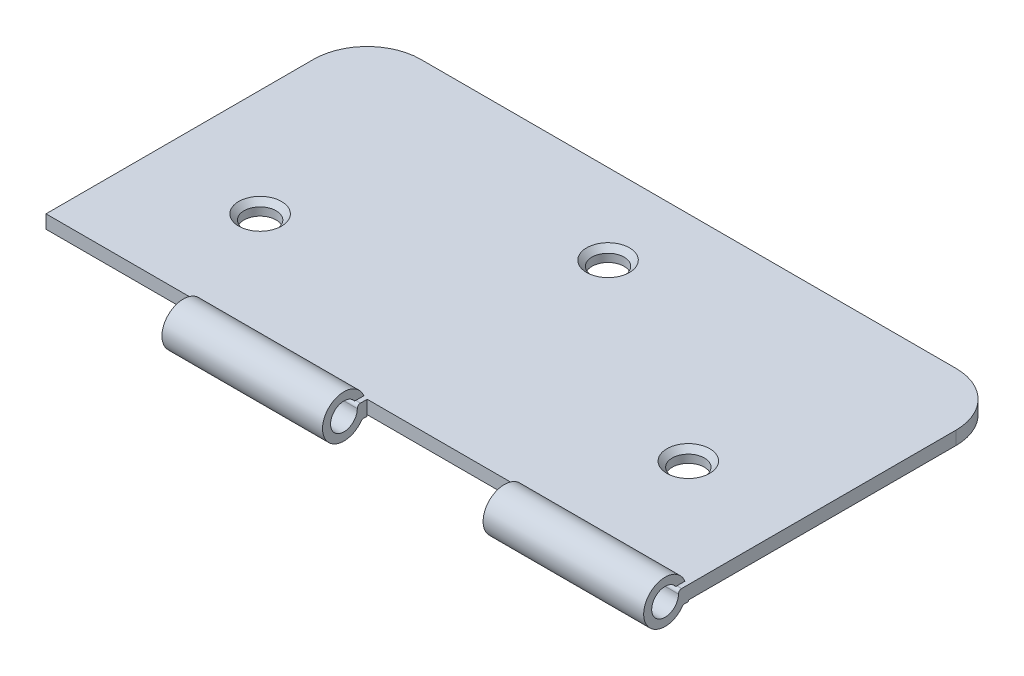
SolidWorks part; units mm, degrees
material "Brass"
ref_plane "Front Plane" through (0, 0, 0) normal (0, 0, 1) x (1, 0, 0)
ref_plane "Top Plane" through (0, 0, 0) normal (0, 1, 0) x (1, 0, 0)
ref_plane "Right Plane" through (0, 0, 0) normal (1, 0, 0) x (0, 0, -1)
sketch "Sketch1" plane through (0, 0, 0) normal (0, 1, 0) x (1, 0, 0)
  line L1 (60, 30) -> (-60, 30)
  line L2 (60, 30) -> (60, -30)
  line L3 (60, -30) -> (-60, -30)
  line L4 (-60, 30) -> (-60, -30)
  line L5 (60, 30) -> (-60, -30) construction
  line L6 (60, -30) -> (-60, 30) construction
  point P0 (0, 0)
  dimension "D1" = 120
  dimension "D2" = 60
extrude "Boss-Extrude1" add sketch "Sketch1" along normal blind 2.5
fillet "Fillet1" radius 10 2 edges at (-60, 1.25, -30) (60, 1.25, -30)
sketch "Sketch2" plane through (60, 0, 0) normal (1, 0, 0) x (0, 0, -1)
  line L0 (-30, 2.5) -> (-30, -0.25)
  line L1 (-30, -0.25) -> (-30.7, -0.25)
  line L2 (-30.625, 3.3684) -> (-32.325, 3.3684)
  line L3 (-30, 2.5) -> (-31.25, 2.5)
  arc A0 (-30.7, -0.25) -> (-31.1047, -0.4564) centre (-30.7, -0.75) ccw
  arc A1 (-31.1047, -0.4564) -> (-30.625, 3.3684) centre (-34.3426, 1.8922) cw
  arc A2 (-31.25, 2.5) -> (-31.8427, 1.9044) centre (-31.25, 1.9073) ccw
  arc A3 (-31.8427, 1.9044) -> (-32.325, 3.3684) centre (-34.3426, 1.8922) cw
  point P6 (-30.3901, 3.8136)
  point P8 (-30.625, 2.5)
  point P9 (0, 0)
  dimension "D1" = 4
  dimension "D2" = 1.7
  dimension "D3" = 0.5
  dimension "D7" = 2.5
  dimension "D4" = 0.7
  dimension "D5" = 1.25
  dimension "D6" = 2.75
extrude "Boss-Extrude2" add sketch "Sketch2" against normal blind 30 separate body
pattern_linear "LPattern1" count 2 spacing 60 along (-1, 0, 0) of bodies 102
sketch "Sketch3" plane through (0, 2.5, 0) normal (0, 1, 0) x (1, 0, 0)
  line L0 (60, -30) -> (60, 20) construction
  line L1 (-60, -30) -> (60, -30) construction
  line L2 (-60, 20) -> (-60, -30) construction
  line L3 (50, 30) -> (-50, 30) construction
  circle A0 centre (40, -10) radius 3
  circle A1 centre (0, 15) radius 3
  circle A2 centre (-40, -10) radius 3
  dimension "D1" = 6
  dimension "D2" = 20
  dimension "D3" = 20
  dimension "D4" = 20
  dimension "D5" = 20
  dimension "D6" = 15
extrude "Cut-Extrude1" cut sketch "Sketch3" against normal through all
chamfer "Chamfer1" distance 1 angle 45 3 edges at (-40, 2.5, 13) (40, 2.5, 13) (0, 2.5, -12)
combine bodies "Combine1" operation type add bodies to combine 103 102 104
